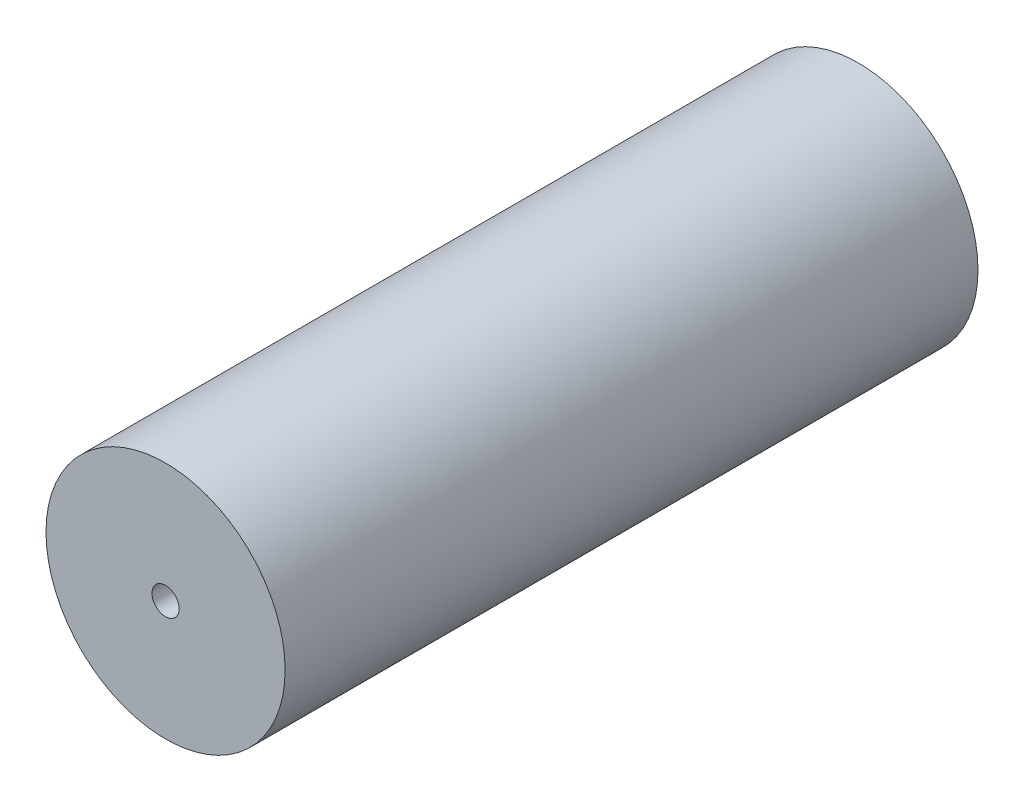
SolidWorks part; units mm, degrees
material "ABS"
ref_plane "Front Plane" through (0, 0, 0) normal (0, 0, 1) x (1, 0, 0)
ref_plane "Top Plane" through (0, 0, 0) normal (0, 1, 0) x (1, 0, 0)
ref_plane "Right Plane" through (0, 0, 0) normal (1, 0, 0) x (0, 0, -1)
sketch "Sketch2" plane through (0, 0, 0) normal (0, 0, 1) x (1, 0, 0)
  circle A0 centre (0, 0) radius 22
  dimension "D1" = 44
extrude "Boss-Extrude1" add sketch "Sketch2" along normal blind 127.5 contours A0
sketch "Sketch3" plane through (0, 0, 0) normal (0, 0, -1) x (-1, 0, 0)
  circle A0 centre (0, 0) radius 2.5
  dimension "D1" = 5
extrude "Cut-Extrude1" cut sketch "Sketch3" against normal blind 135
sketch "Sketch5" plane through (0, 0, 0) normal (0, 0, -1) x (-1, 0, 0)
  circle A0 centre (0, 0) radius 17.5
  dimension "D1" = 35
extrude "Cut-Extrude2" cut sketch "Sketch5" against normal blind 30
